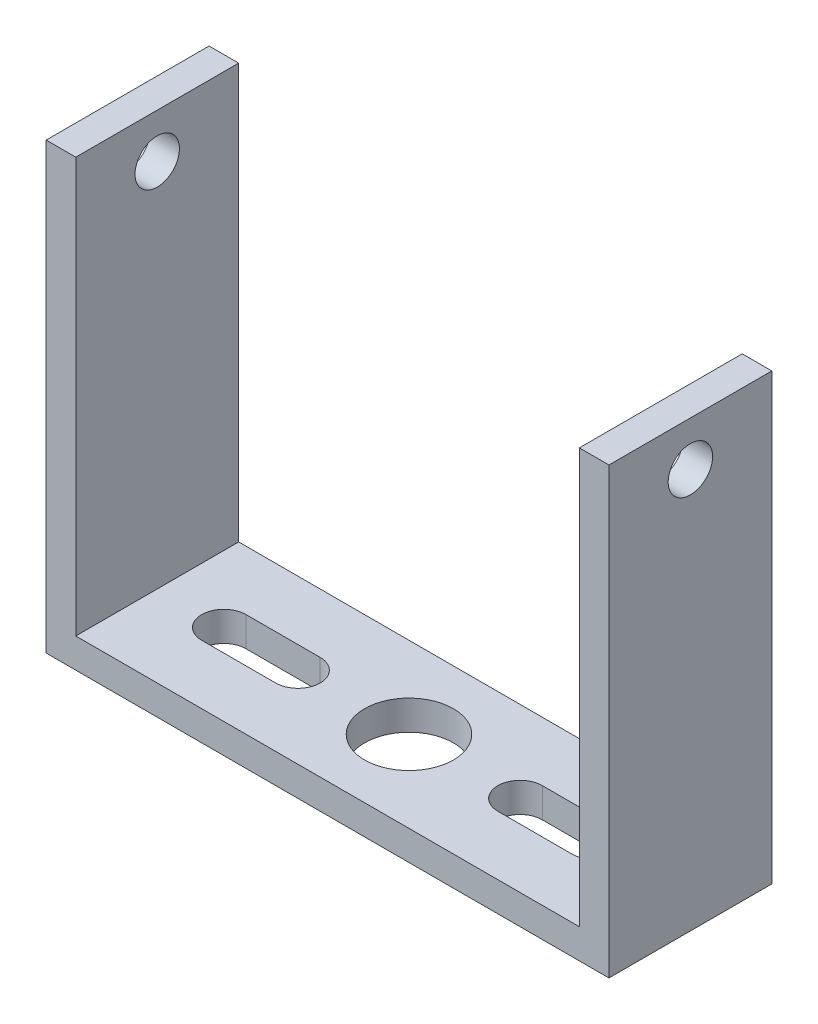
SolidWorks part; units mm, degrees
material "2014-O"
ref_plane "前视基准面" through (0, 0, 0) normal (0, 0, 1) x (1, 0, 0)
ref_plane "上视基准面" through (0, 0, 0) normal (0, 1, 0) x (1, 0, 0)
ref_plane "右视基准面" through (0, 0, 0) normal (1, 0, 0) x (0, 0, -1)
other "Configuration Table"
sketch "草图2" plane through (0, 0, 0) normal (0, 0, 1) x (1, 0, 0)
  line L0 (0, 30) -> (0, 0)
  line L1 (0, 0) -> (38, 0)
  line L2 (38, 0) -> (38, 30)
  line L3 (38, 30) -> (36, 30)
  line L4 (36, 30) -> (36, 2)
  line L5 (36, 2) -> (2, 2)
  line L6 (2, 2) -> (2, 30)
  line L7 (2, 30) -> (0, 30)
  dimension "D1" = 38
  dimension "D2" = 2
  dimension "D3" = 30
  dimension "D4" = 2
extrude "凸台-拉伸1" add sketch "草图2" along normal blind 11
sketch "草图3" plane through (0, 0, 0) normal (-1, 0, 0) x (0, 0, 1)
  line L0 (11, 0) -> (0, 0) construction
  line L1 (11, 30) -> (11, 0) construction
  circle A0 centre (5.5, 27) radius 1.5
  dimension "D3" = 3
  dimension "D1" = 27
  dimension "D2" = 5.5
extrude "切除-拉伸1" cut sketch "草图3" against normal through all both and the other way through all
sketch "草图4" plane through (0, 0, 0) normal (0, -1, 0) x (1, 0, 0)
  line L0 (0, 11) -> (0, 0) construction
  line L1 (0, 5.5) -> (38, 5.5) construction
  line L2 (38, 11) -> (38, 0) construction
  line L3 (0, 11) -> (38, 11) construction
  line L4 (19, 11) -> (19, 0) construction
  line L5 (0, 0) -> (38, 0) construction
  line L6 (26.5, 5.5) -> (31.5, 5.5) construction
  line L7 (26.5, 7) -> (31.5, 7)
  line L8 (26.5, 4) -> (31.5, 4)
  line L9 (6.5, 5.5) -> (11.5, 5.5) construction
  line L10 (6.5, 7) -> (11.5, 7)
  line L11 (6.5, 4) -> (11.5, 4)
  circle A0 centre (19, 5.5) radius 3
  arc A1 (26.5, 7) -> (26.5, 4) centre (26.5, 5.5) ccw
  arc A2 (31.5, 4) -> (31.5, 7) centre (31.5, 5.5) ccw
  arc A3 (6.5, 7) -> (6.5, 4) centre (6.5, 5.5) ccw
  arc A4 (11.5, 4) -> (11.5, 7) centre (11.5, 5.5) ccw
  point P16 (29, 5.5)
  point P21 (9, 5.5)
  point P28 (29.0889, 5.5)
  dimension "D1" = 6
  dimension "D2" = 1.5
  dimension "D3" = 5
  dimension "D4" = 25
  dimension "D5" = 9
extrude "切除-拉伸2" cut sketch "草图4" against normal blind 3
